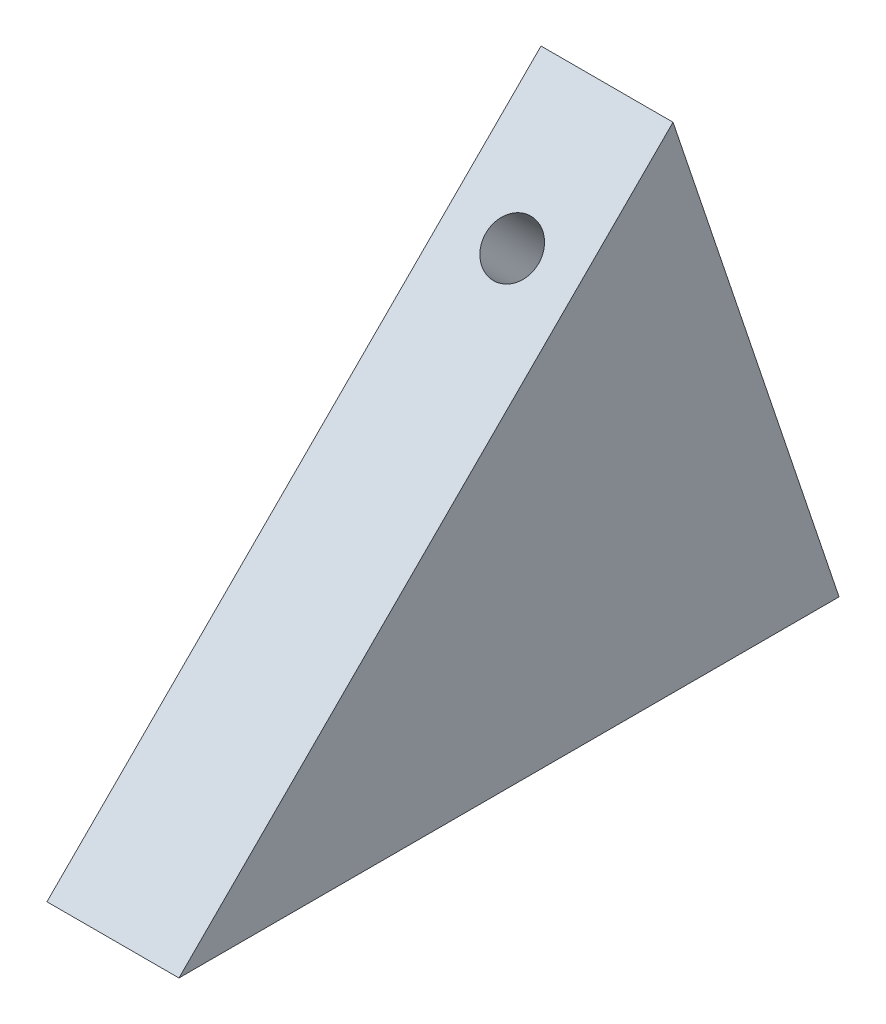
SolidWorks part; units mm, degrees
ref_plane "Alzado" through (0, 0, 0) normal (0, 0, 1) x (1, 0, 0)
ref_plane "Planta" through (0, 0, 0) normal (0, 1, 0) x (1, 0, 0)
ref_plane "Vista lateral" through (0, 0, 0) normal (1, 0, 0) x (0, 0, -1)
sketch "Croquis1" plane through (0, 0, 0) normal (1, 0, 0) x (0, 0, -1)
  line L0 (0, 0) -> (37.4242, 37.4242)
  line L1 (37.4242, 37.4242) -> (50, 0)
  line L2 (50, 0) -> (0, 0)
  dimension "D1" = 50
  dimension "D2" = 45
extrude "Saliente-Extruir1" add sketch "Croquis1" along normal blind 10
sketch "Croquis2" plane through (0, 0, 0) normal (0, -1, 0) x (1, 0, 0)
  line L0 (10, 0) -> (0, 0) construction
  circle A0 centre (5, -34.4777) radius 2
  point P4 (5, 0)
  dimension "D1" = 4
extrude "Cortar-Extruir1" cut sketch "Croquis2" against normal blind 10
sketch "Croquis3" plane through (0, 0, 0) normal (0, 0.7071, 0.7071) x (1, 0, 0)
  line L0 (10, 0) -> (0, 0) construction
  circle A0 centre (5, 42.7665) radius 2
  point P4 (5, 0)
  dimension "D1" = 4
extrude "Cortar-Extruir2" cut sketch "Croquis3" against normal blind 10
